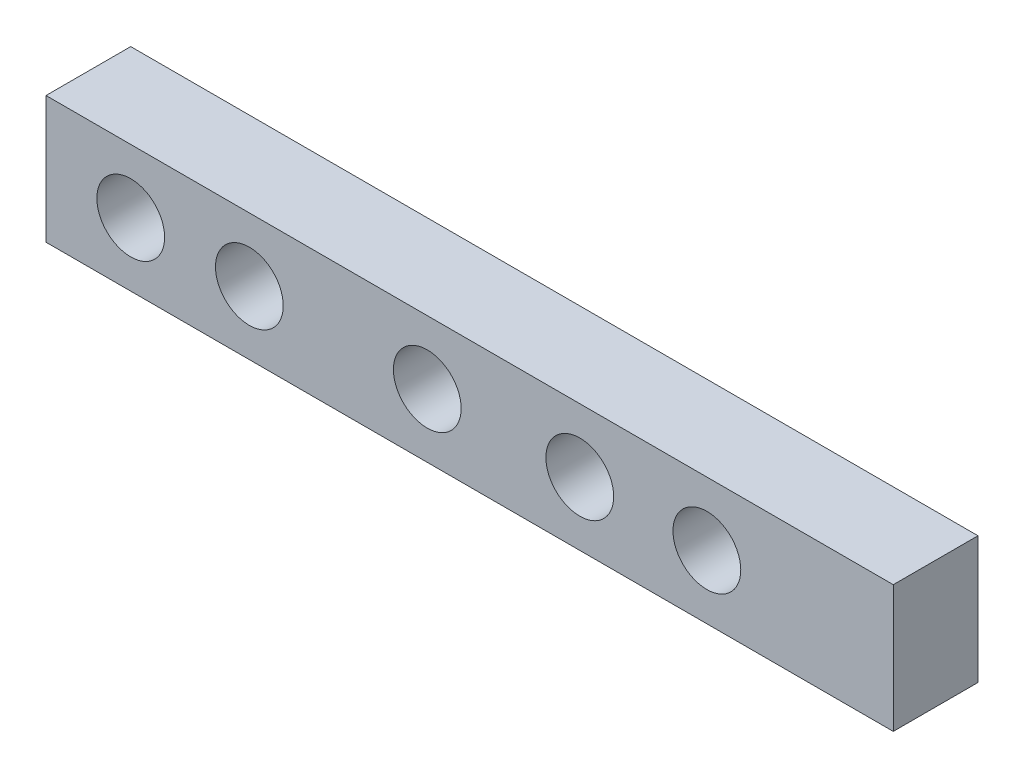
SolidWorks part; units mm, degrees
material "Сталь"
ref_plane "Спереди" through (0, 0, 0) normal (0, 0, 1) x (1, 0, 0)
ref_plane "Сверху" through (0, 0, 0) normal (0, 1, 0) x (1, 0, 0)
ref_plane "Справа" through (0, 0, 0) normal (1, 0, 0) x (0, 0, -1)
sketch "Эскиз1" plane through (0, 0, 0) normal (0, 0, 1) x (1, 0, 0)
  line L0 (-50, 0) -> (50, 0) construction
  line L1 (-50, -7.5) -> (50, -7.5)
  line L2 (-50, -7.5) -> (-50, 7.5)
  line L3 (-50, 7.5) -> (50, 7.5)
  line L4 (50, -7.5) -> (50, 7.5)
  line L5 (-50, -7.5) -> (50, 7.5) construction
  line L6 (-50, 7.5) -> (50, -7.5) construction
  point P0 (0, 0)
  dimension "D1" = 100
  dimension "D2" = 15
extrude "Бобышка-Вытянуть1" add sketch "Эскиз1" along normal blind 10
sketch "Эскиз2" [suppressed] plane through (0, 0, 10) normal (0, 0, 1) x (1, 0, 0)
  line L0 (-50, 0) -> (50, 0) construction
  line L1 (-50, -10) -> (-50, 10) construction
  line L2 (50, -10) -> (50, 10) construction
  circle A0 centre (-40, 0) radius 4
  circle A1 centre (-26, 0) radius 4
  circle A2 centre (-5, 0) radius 4
  circle A3 centre (13, 0) radius 4
  circle A4 centre (28, 0) radius 4
  dimension "D1" = 8
  dimension "D2" = 10
  dimension "D5" = 63
  dimension "D6" = 78
  dimension "D3" = 24
  dimension "D4" = 45
extrude "Вырез-Вытянуть1" [suppressed] cut sketch "Эскиз2" against normal through all
sketch "Эскиз3" [suppressed] plane through (0, 0, 10) normal (0, 0, 1) x (1, 0, 0)
  line L0 (-50, 0) -> (50, 0) construction
  line L1 (-50, -10) -> (-50, 10) construction
  line L2 (50, -10) -> (50, 10) construction
  circle A0 centre (-40, 0) radius 4
  dimension "D1" = 8
  dimension "D2" = 10
extrude "Вырез-Вытянуть2" [suppressed] cut sketch "Эскиз3" against normal blind 10
pattern_linear "Линейный массив1" [suppressed] count 9 spacing 10
sketch "Эскиз4" plane through (0, 0, 10) normal (0, 0, 1) x (1, 0, 0)
  line L0 (-50, 0) -> (50, 0) construction
  line L1 (50, -7.5) -> (50, 7.5) construction
  line L2 (-50, -7.5) -> (-50, 7.5) construction
  circle A0 centre (-40, 0) radius 4
  circle A1 centre (-26, 0) radius 4
  circle A2 centre (-5, 0) radius 4
  circle A3 centre (13, 0) radius 4
  circle A4 centre (28, 0) radius 4
  dimension "D6" = 8
  dimension "D1" = 10
  dimension "D2" = 24
  dimension "D3" = 45
  dimension "D4" = 63
  dimension "D5" = 78
extrude "Вырез-Вытянуть3" cut sketch "Эскиз4" against normal through all
